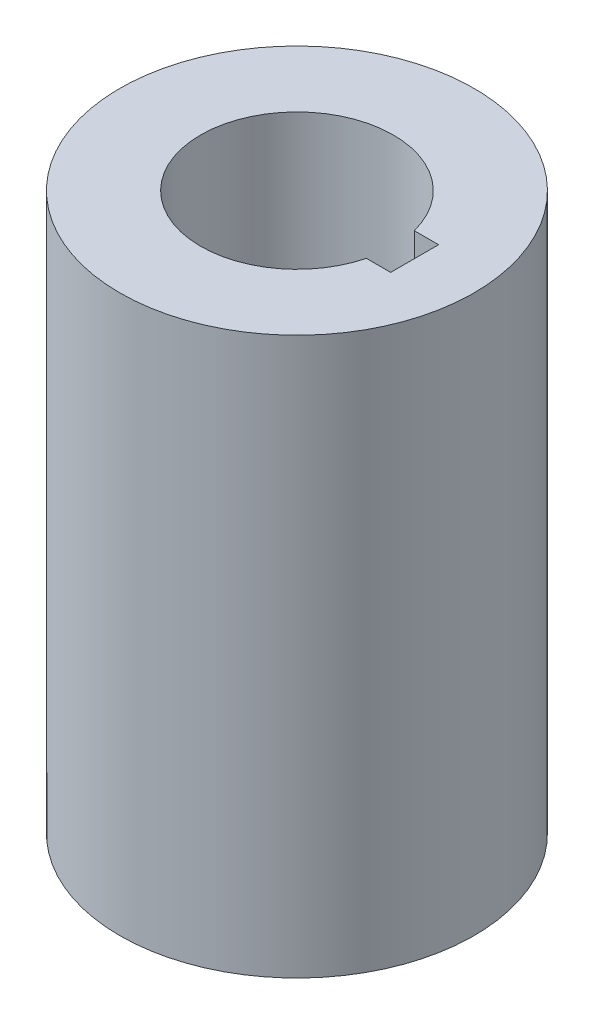
SolidWorks part; units mm, degrees
ref_plane "Front Plane" through (0, 0, 0) normal (0, 0, 1) x (1, 0, 0)
ref_plane "Top Plane" through (0, 0, 0) normal (0, 1, 0) x (1, 0, 0)
ref_plane "Right Plane" through (0, 0, 0) normal (1, 0, 0) x (0, 0, -1)
sketch "Sketch1" plane through (0, 0, 0) normal (0, 1, 0) x (1, 0, 0)
  circle A0 centre (0, 0) radius 17.5
extrude "Boss-Extrude1" add sketch "Sketch1" along normal blind 55
sketch "Sketch2" plane through (0, 55, 0) normal (0, 1, 0) x (1, 0, 0)
  circle A0 centre (0, 0) radius 9.525
extrude "Cut-Extrude1" cut sketch "Sketch2" against normal blind 23
sketch "Sketch3" plane through (0, 32, 0) normal (0, 1, 0) x (1, 0, 0)
  line L0 (0, 0) -> (25.1788, 0) construction
  line L1 (9.525, 2.37) -> (11.625, 2.37)
  line L2 (6.895, 2.37) -> (6.895, -2.3669)
  line L3 (9.525, 2.37) -> (6.895, 2.37)
  line L4 (6.895, -2.3669) -> (11.625, -2.3669)
  line L5 (11.625, -2.3669) -> (11.625, 2.37)
extrude "Cut-Extrude2" cut sketch "Sketch3" along normal up to next
sketch "Sketch5" plane through (0, 0, 0) normal (0, -1, 0) x (-1, 0, 0)
  circle A0 centre (0, 0) radius 6
extrude "Cut-Extrude3" cut sketch "Sketch5" against normal blind 23
